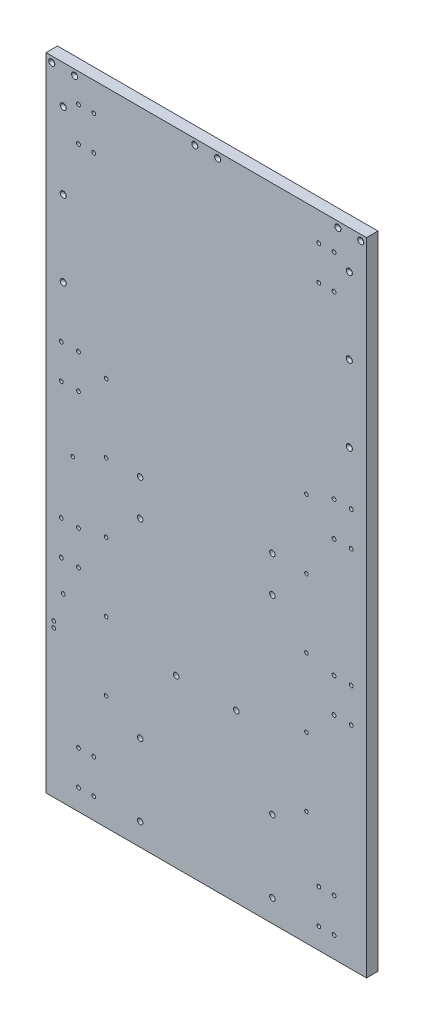
SolidWorks part; units mm, degrees
material "Beech"
ref_plane "Front Plane" through (0, 0, 0) normal (0, 0, 1) x (1, 0, 0)
ref_plane "Top Plane" through (0, 0, 0) normal (0, 1, 0) x (1, 0, 0)
ref_plane "Right Plane" through (0, 0, 0) normal (1, 0, 0) x (0, 0, -1)
sketch "Sketch1" plane through (0, 0, 0) normal (0, 0, 1) x (1, 0, 0)
  line L8 (266.573, 7002.78) -> (-266.573, 7002.78)
  line L9 (-266.573, 7002.78) -> (-266.573, 5935.98)
  line L10 (-266.573, 5935.98) -> (266.573, 5935.98)
  line L11 (266.573, 5935.98) -> (266.573, 7002.78)
  point P2 (0, 7002.78)
  dimension "D1" = 1066.8
  dimension "D2" = 533.146
extrude "Boss-Extrude1" add sketch "Sketch1" against normal blind 19.05
hole_wizard "23/64 (0.35938) Diameter Hole1" positions "Sketch2" profile "Sketch3" hole size "23/64" standard "ANSI Inch" end condition through all
sketch "Sketch2" plane through (0, 0, -19.05) normal (0, 0, -1) x (-1, 0, 0)
  point P15 (110, 5973.262)
  point P18 (110, 6093.262)
  point P21 (-110, 6093.262)
  point P24 (-110, 5973.262)
  point P27 (-50, 6213.262)
  point P30 (50, 6213.262)
  point P33 (-110, 6409.662)
  point P36 (-110, 6469.662)
  point P39 (110, 6409.662)
  point P42 (110, 6469.662)
sketch "Sketch3" plane through (-110, 5973.262, -19.05) normal (1, 0, 0) x (0, 1, 0)
  line L0 (0, 0) -> (0, 19.05)
  line L1 (0, 19.05) -> (4.5641, 19.05)
  line L2 (4.5641, 19.05) -> (4.5641, 0)
  line L5 (4.5641, 0) -> (0, 0)
  line L11 (0, -6.35) -> (0, 107.95) construction
  dimension "Thru Hole Dia." = 9.1283
  dimension "Thru Hole Depth" = 19.05
sketch "Sketch4" plane through (0, 0, 0) normal (0, 0, 1) x (1, 0, 0)
  line L0 (-266.573, 7002.78) -> (-266.573, 5935.98) construction
  line L1 (-266.573, 5935.98) -> (-222.123, 5935.98)
  line L2 (-266.573, 5935.98) -> (-266.573, 6012.18)
  line L3 (-266.573, 6012.18) -> (-222.123, 6012.18)
  line L4 (-222.123, 5935.98) -> (-222.123, 6012.18)
  line L5 (-266.573, 7002.78) -> (-222.123, 7002.78)
  line L6 (-266.573, 7002.78) -> (-266.573, 6926.58)
  line L7 (-266.573, 6926.58) -> (-222.123, 6926.58)
  line L8 (-222.123, 7002.78) -> (-222.123, 6926.58)
  line L9 (266.573, 7002.78) -> (-266.573, 7002.78) construction
  line L10 (266.573, 5935.98) -> (266.573, 7002.78) construction
  line L11 (266.573, 7002.78) -> (222.123, 7002.78)
  line L12 (266.573, 7002.78) -> (266.573, 6926.58)
  line L13 (266.573, 6926.58) -> (222.123, 6926.58)
  line L14 (222.123, 7002.78) -> (222.123, 6926.58)
  line L15 (-266.573, 5935.98) -> (266.573, 5935.98) construction
  line L16 (266.573, 5935.98) -> (222.123, 5935.98)
  line L17 (266.573, 5935.98) -> (266.573, 6012.18)
  line L18 (266.573, 6012.18) -> (222.123, 6012.18)
  line L19 (222.123, 5935.98) -> (222.123, 6012.18)
  dimension "D1" = 76.2
  dimension "D2" = 44.45
split line "Split Line1" [suppressed]
hole_wizard "15/64 (0.23438) Diameter Hole1" positions "Sketch5" profile "Sketch6" hole size "15/64" standard "ANSI Inch" end condition through all
sketch "Sketch5" plane through (0, 0, -19.05) normal (0, 0, -1) x (-1, 0, 0)
  point P0 (166.6875, 6125.8958)
  point P2 (166.6875, 6240.1958)
  point P4 (166.6875, 6354.4958)
  point P6 (166.6875, 6468.7958)
  point P8 (166.6875, 6583.0958)
  point P14 (-166.6875, 6125.8958)
  point P16 (-166.6875, 6240.1958)
  point P18 (-166.6875, 6354.4958)
  point P20 (-166.6875, 6468.7958)
  point P22 (-166.6875, 6583.0958)
sketch "Sketch6" plane through (-166.6875, 6125.8958, -19.05) normal (1, 0, 0) x (0, 1, 0)
  line L0 (0, 0) -> (0, 19.05)
  line L1 (0, 19.05) -> (2.9766, 19.05)
  line L2 (2.9766, 19.05) -> (2.9766, 0)
  line L5 (2.9766, 0) -> (0, 0)
  line L11 (0, -6.35) -> (0, 107.95) construction
  dimension "Thru Hole Dia." = 5.9533
  dimension "Thru Hole Depth" = 19.05
hole_wizard "1/4 (0.25) Diameter Hole1" positions "Sketch9" profile "Sketch10" hole size "1/4" standard "ANSI Inch" end condition through all
sketch "Sketch9" plane through (0, 0, 0) normal (0, 0, 1) x (1, 0, 0)
  line L0 (0, 7002.78) -> (0, 5935.98) construction
  line L1 (-266.573, 5935.98) -> (266.573, 5935.98) construction
  point P0 (-212.598, 6955.155)
  point P2 (-212.598, 6898.005)
  point P4 (-187.198, 6898.005)
  point P6 (-187.198, 6955.155)
  point P12 (-241.173, 6598.9708)
  point P14 (-241.173, 6541.8208)
  point P16 (-212.598, 6541.8208)
  point P18 (-212.598, 6598.9708)
  point P24 (-212.598, 6344.9708)
  point P26 (-241.173, 6344.9708)
  point P28 (-241.173, 6287.8208)
  point P30 (-212.598, 6287.8208)
  point P36 (-212.598, 6028.055)
  point P38 (-187.198, 6028.055)
  point P40 (-187.198, 5970.905)
  point P42 (-212.598, 5970.905)
  point P55 (212.598, 5970.905)
  point P56 (187.198, 5970.905)
  point P57 (187.198, 6028.055)
  point P58 (212.598, 6028.055)
  point P59 (212.598, 6287.8208)
  point P60 (241.173, 6287.8208)
  point P61 (241.173, 6344.9708)
  point P62 (212.598, 6344.9708)
  point P63 (212.598, 6598.9708)
  point P64 (212.598, 6541.8208)
  point P65 (241.173, 6541.8208)
  point P66 (241.173, 6598.9708)
  point P67 (187.198, 6955.155)
  point P68 (187.198, 6898.005)
  point P69 (212.598, 6898.005)
  point P70 (212.598, 6955.155)
sketch "Sketch10" plane through (-212.598, 6955.155, 0) normal (1, 0, 0) x (0, -1, 0)
  line L0 (0, 0) -> (0, 19.05)
  line L1 (0, 19.05) -> (3.175, 19.05)
  line L2 (3.175, 19.05) -> (3.175, 0)
  line L5 (3.175, 0) -> (0, 0)
  line L11 (0, -6.35) -> (0, 107.95) construction
  dimension "Thru Hole Dia." = 6.35
  dimension "Thru Hole Depth" = 19.05
hole_wizard "15/64 (0.23438) Diameter Hole2" positions "Sketch11" profile "Sketch12" hole size "15/64" standard "ANSI Inch" end condition through all
sketch "Sketch11" plane through (0, 0, -19.05) normal (0, 0, -1) x (-1, 0, 0)
  line L0 (252.423, 6180.33) -> (255.223, 6180.33) construction
  line L2 (252.423, 6190.33) -> (255.223, 6190.33) construction
  line L3 (266.573, 5935.98) -> (-266.573, 5935.98) construction
  line L4 (266.573, 7002.78) -> (266.573, 5935.98) construction
  point P11 (253.823, 6180.33)
  point P13 (253.823, 6190.33)
  point P14 (237.948, 6237.3129)
  point P16 (222.123, 6442.7873)
  dimension "D1" = 206.0829
  dimension "D2" = 301.3329
  dimension "D3" = 28.625
  dimension "D4" = 44.45
sketch "Sketch12" plane through (-222.123, 6442.7873, -19.05) normal (1, 0, 0) x (0, 1, 0)
  line L0 (0, 0) -> (0, 19.05)
  line L1 (0, 19.05) -> (2.9766, 19.05)
  line L2 (2.9766, 19.05) -> (2.9766, 0)
  line L5 (2.9766, 0) -> (0, 0)
  line L11 (0, -6.35) -> (0, 107.95) construction
  dimension "Thru Hole Dia." = 5.9533
  dimension "Thru Hole Depth" = 19.05
hole_wizard "Hole1" positions "Sketch13" profile "Sketch14" legacy
sketch "Sketch13" plane through (0, 0, 0) normal (0, 0, 1) x (1, 0, 0)
  line L0 (0, 7002.78) -> (0, 5935.98) construction
  line L4 (237.998, 7002.78) -> (237.998, 5935.98) construction
  line L8 (266.573, 6993.255) -> (0, 6993.255) construction
  line L12 (237.998, 6939.28) -> (237.998, 6686.1919)
  point P26 (237.998, 6686.1919)
  point P27 (257.048, 6993.255)
  point P29 (218.948, 6993.255)
  point P31 (19.05, 6993.255)
  point P35 (237.998, 6939.28)
  point P42 (237.998, 6812.7359)
  point P51 (-237.998, 6812.7359)
  point P52 (-237.998, 6939.28)
  point P53 (-19.05, 6993.255)
  point P54 (-218.948, 6993.255)
  point P55 (-257.048, 6993.255)
  point P56 (-237.998, 6686.1919)
sketch "Sketch14" plane through (-237.998, 6686.1919, 0) normal (1, 0, 0) x (0, -1, 0)
  line L0 (0, 0) -> (0, 39.0539)
  line L1 (0, 39.0539) -> (1.5875, 38.1)
  line L2 (1.5875, 38.1) -> (1.5875, 4.0177)
  line L3 (1.5875, 4.0177) -> (5.08, 0)
  line L4 (5.08, 0) -> (0, 0)
  line L5 (0, -14.3089) -> (0, 102.4216) construction
  line L6 (0, 39.0539) -> (-1.5875, 38.1) construction
  line L7 (-1.5875, 4.0177) -> (-5.08, 0) construction
  dimension "Diameter" = 3.175
  dimension "Depth" = 38.1
  dimension "C-Sink Diameter" = 10.16
  dimension "C-Sink Angle" = 82
  dimension "Drill Angle" = 118
